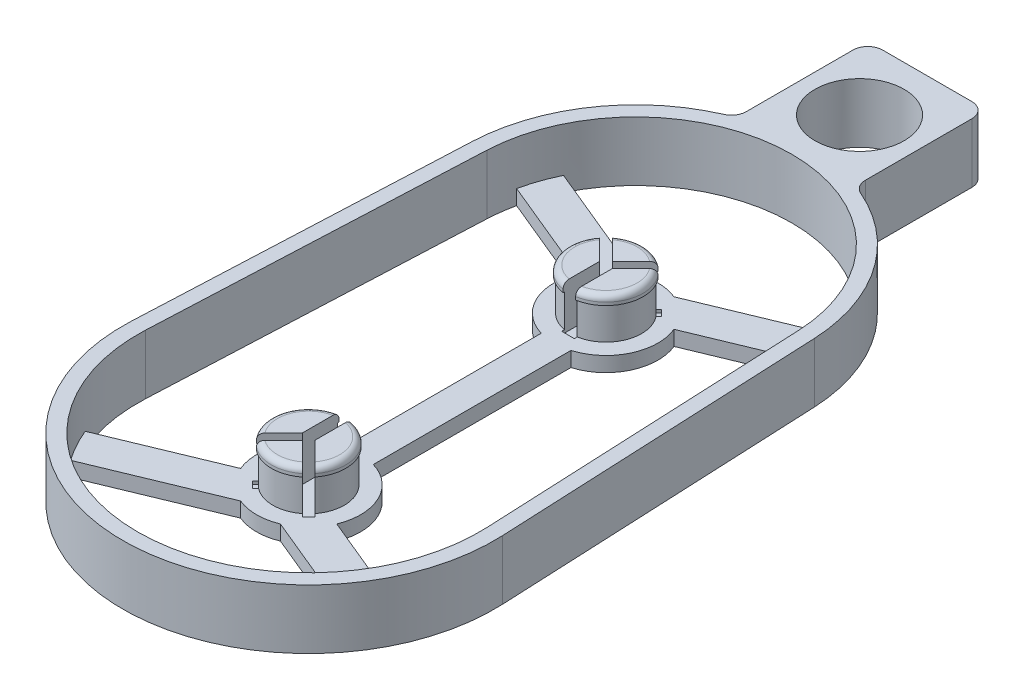
SolidWorks part; units mm, degrees
ref_plane "Alzado" through (0, 0, 0) normal (0, 0, 1) x (1, 0, 0)
ref_plane "Planta" through (0, 0, 0) normal (0, 1, 0) x (1, 0, 0)
ref_plane "Vista lateral" through (0, 0, 0) normal (1, 0, 0) x (0, 0, -1)
sketch "Croquis1" plane through (0, 0, 0) normal (0, 1, 0) x (1, 0, 0)
  line L0 (-52.4457, 112.3864) -> (-57.4406, 2.6136)
  line L3 (52.4457, 112.3864) -> (57.4406, 2.6136)
  line L4 (-57.4406, 112.6136) -> (-62.4354, 2.8409)
  line L5 (57.4406, 112.6136) -> (62.4354, 2.8409)
  line L6 (-0.0609, 208.1187) -> (0, 162.5) construction
  line L7 (-20.0609, 185.1871) -> (19.9391, 185.2137) construction
  line L9 (-20.0609, 167.2556) -> (-20.0609, 203.1187)
  line L10 (-15.0609, 208.1187) -> (14.9391, 208.1187)
  line L11 (19.9391, 203.1187) -> (19.9391, 167.3087)
  arc A2 (-57.4406, 2.6136) -> (57.4406, 2.6136) centre (0, 0) ccw
  arc A3 (52.4457, 112.3864) -> (-52.4457, 112.3864) centre (0, 110) ccw
  arc A4 (-62.4354, 2.8409) -> (62.4354, 2.8409) centre (0, 0) ccw
  arc A5 (-23.056, 162.6751) -> (-57.4406, 112.6136) centre (0, 110) ccw
  arc A7 (14.9391, 208.1187) -> (19.9391, 203.1187) centre (14.9391, 203.1187) cw
  arc A8 (-20.0609, 203.1187) -> (-15.0609, 208.1187) centre (-15.0609, 203.1187) cw
  arc A9 (57.4406, 112.6136) -> (-57.4406, 112.6136) centre (0, 110) ccw construction
  arc A10 (-23.056, 162.6751) -> (-20.0609, 167.2556) centre (-25.0609, 167.2556) ccw
  arc A11 (-23.056, 162.6751) -> (-57.4406, 112.6136) centre (0, 110) ccw construction
  arc A12 (57.4406, 112.6136) -> (22.944, 162.724) centre (0, 110) ccw
  arc A13 (19.9391, 167.3087) -> (22.944, 162.724) centre (24.9391, 167.3087) ccw
  point P25 (19.9391, 163.9322)
  dimension "D1" = 115
  dimension "D2" = 105
  dimension "D4" = 5
  dimension "D5" = 5
  dimension "D6" = 5
  dimension "D3" = 5
extrude "Saliente-Extruir1" add sketch "Croquis1" along normal blind 20
ref_plane "Plano1" through (0, 0, 0) normal (0, -1, 0) x (-1, 0, 0)
sketch "Croquis2" plane through (0, 0, 0) normal (0, -1, 0) x (-1, 0, 0)
  line L4 (0, 88.9579) -> (0, 75.244) construction
  line L5 (-5, 83.2295) -> (-5, 75.244) construction
  line L6 (5, 83.2295) -> (5, 75.244) construction
  line L7 (5, 83.2295) -> (5, 16.7705)
  line L8 (-5, 83.2295) -> (-5, 16.7705)
  line L11 (0, 100) -> (12.3744, 112.3744) construction
  line L12 (-17.5, 100) -> (17.5, 100) construction
  line L13 (16.1679, 106.697) -> (51.2823, 121.2418)
  line L14 (0, 100) -> (16.1679, 106.697) construction
  line L15 (0, 100) -> (6.697, 116.1679) construction
  line L16 (6.697, 116.1679) -> (47.2172, 132.9519)
  line L17 (0, 100) -> (-16.1679, 106.697) construction
  line L18 (0, 100) -> (-12.3744, 112.3744) construction
  line L19 (0, 100) -> (-6.697, 116.1679) construction
  line L20 (-16.1679, 106.697) -> (-51.2823, 121.2418)
  line L21 (-6.697, 116.1679) -> (-47.2172, 132.9519)
  line L22 (5, 50) -> (-5, 50) construction
  line L23 (-17.5, 0) -> (17.5, 0) construction
  line L24 (0, 0) -> (0, -17.5) construction
  line L25 (0, 0) -> (12.3744, -12.3744) construction
  line L26 (0, 0) -> (16.1679, -6.697) construction
  line L27 (0, 0) -> (6.697, -16.1679) construction
  line L28 (0, 0) -> (-16.1679, -6.697) construction
  line L29 (0, 0) -> (-6.697, -16.1679) construction
  line L30 (16.1679, -6.697) -> (53.1231, -22.0043)
  line L31 (6.697, -16.1679) -> (47.1429, -32.9211)
  line L32 (-16.1679, -6.697) -> (-53.1231, -22.0043)
  line L33 (-6.697, -16.1679) -> (-47.1429, -32.9211)
  circle A0 centre (0, 0) radius 50 construction
  circle A1 centre (0, 100) radius 50 construction
  arc A2 (5, 83.2295) -> (16.1679, 106.697) centre (0, 100) ccw
  arc A3 (-5, 16.7705) -> (-16.1679, -6.697) centre (0, 0) ccw
  arc A4 (52.4457, 112.3864) -> (-52.4457, 112.3864) centre (0, 110) ccw construction
  arc A5 (52.4457, 112.3864) -> (-52.4457, 112.3864) centre (0, 110) ccw construction
  arc A7 (6.697, 116.1679) -> (-6.697, 116.1679) centre (0, 100) ccw
  arc A8 (51.2823, 121.2418) -> (47.2172, 132.9519) centre (0, 110) ccw
  arc A9 (-47.2172, 132.9519) -> (-51.2823, 121.2418) centre (0, 110) ccw
  arc A10 (-16.1679, 106.697) -> (-5, 83.2295) centre (0, 100) ccw
  arc A11 (-57.4406, 2.6136) -> (57.4406, 2.6136) centre (0, 0) ccw construction
  arc A13 (-53.1231, -22.0043) -> (-47.1429, -32.9211) centre (0, 0) ccw
  arc A14 (47.1429, -32.9211) -> (53.1231, -22.0043) centre (0, 0) ccw
  arc A15 (16.1679, -6.697) -> (5, 16.7705) centre (0, 0) ccw
  arc A16 (-6.697, -16.1679) -> (6.697, -16.1679) centre (0, 0) ccw
  point P2 (0, 0)
  point P41 (0, 0)
  dimension "D1" = 45
  dimension "D2" = 22.5
  dimension "D3" = 35
  dimension "D4" = 5
  dimension "D5" = 5
  dimension "D6" = 45
  dimension "D7" = 22.5
  dimension "D8" = 22.5
  dimension "D9" = 22.5
extrude "Saliente-Extruir2" add sketch "Croquis2" against normal blind 5 separate body
sketch "Sketch1" plane through (0, 5, 0) normal (0, 1, 0) x (1, 0, 0)
  circle A0 centre (0, 100) radius 12
  circle A1 centre (0, 0) radius 12
  dimension "D1" = 24
extrude "Boss-Extrude1" add sketch "Sketch1" along normal blind 11
ref_plane "Plane1" through (0, 16, 0) normal (0, 1, 0) x (1, 0, 0)
sketch "Sketch2" plane through (0, 16, 0) normal (0, 1, 0) x (1, 0, 0)
  circle A0 centre (0, 100) radius 12.5
  circle A1 centre (0, 0) radius 12.5
  dimension "D1" = 25
extrude "Boss-Extrude2" add sketch "Sketch2" along normal blind 3
fillet "Fillet1" radius 2 2 edges at (0, 19, -87.5) (0, 19, 12.5)
ref_plane "Plane2" through (0, 19, 0) normal (0, 1, 0) x (1, 0, 0)
sketch "Sketch6" plane through (0, 19, 0) normal (0, 1, 0) x (1, 0, 0)
  line L0 (-10.5, 100) -> (10.5, 100) construction
  line L1 (0, 100) -> (0, 89.5) construction
  line L2 (0, 100) -> (-7.4246, 107.4246) construction
  line L3 (0, 100) -> (7.4246, 107.4246) construction
  line L4 (-10.5145, 108.3932) -> (-2.1213, 100)
  line L5 (-8.3545, 110.4758) -> (0, 102.1213)
  line L6 (-2.1213, 100) -> (-2.1213, 87.2307)
  line L7 (2.1213, 100) -> (2.1213, 87.2307)
  line L8 (2.1213, 100) -> (10.4254, 108.3041)
  line L9 (0, 102.1213) -> (8.2705, 110.3918)
  line L10 (-10.5145, 108.3932) -> (-8.3545, 110.4758)
  line L11 (8.2705, 110.3918) -> (10.4254, 108.3041)
  line L12 (-2.1213, 87.2307) -> (2.1213, 87.2307)
  line L13 (-5, 50) -> (5, 50) construction
  line L14 (-5, 16.7705) -> (-5, 83.2295) construction
  line L15 (5, 83.2295) -> (5, 16.7705) construction
  line L16 (-2.1213, 12.7693) -> (2.1213, 12.7693)
  line L17 (2.1213, 0) -> (2.1213, 12.7693)
  line L18 (-2.1213, 0) -> (-2.1213, 12.7693)
  line L19 (-10.5145, -8.3932) -> (-2.1213, 0)
  line L20 (-8.3545, -10.4758) -> (0, -2.1213)
  line L21 (0, -2.1213) -> (8.2705, -10.3918)
  line L22 (2.1213, 0) -> (10.4254, -8.3041)
  line L23 (8.2705, -10.3918) -> (10.4254, -8.3041)
  line L24 (-10.5145, -8.3932) -> (-8.3545, -10.4758)
  circle A0 centre (0, 100) radius 10.5 construction
  dimension "D1" = 45
  dimension "D2" = 45
  dimension "D3" = 1.5
  dimension "D4" = 1.5
  dimension "D5" = 1.5
extrude "Cut-Extrude2" cut sketch "Sketch6" against normal blind 15
sketch "Sketch7" plane through (0, 20, 0) normal (0, 1, 0) x (1, 0, 0)
  line L0 (-0.0609, 208.1187) -> (0, 162.5) construction
  line L1 (14.9391, 208.1187) -> (-15.0609, 208.1187) construction
  line L2 (-20.0609, 185.1871) -> (19.9391, 185.2137) construction
  line L3 (-20.0609, 203.1187) -> (-20.0609, 167.2556) construction
  line L4 (19.9391, 167.3087) -> (19.9391, 203.1187) construction
  arc A0 (52.4457, 112.3864) -> (-52.4457, 112.3864) centre (0, 110) ccw construction
  circle A1 centre (-0.0304, 185.3093) radius 15
  dimension "D1" = 30
extrude "Cut-Extrude3" cut sketch "Sketch7" against normal blind 28
